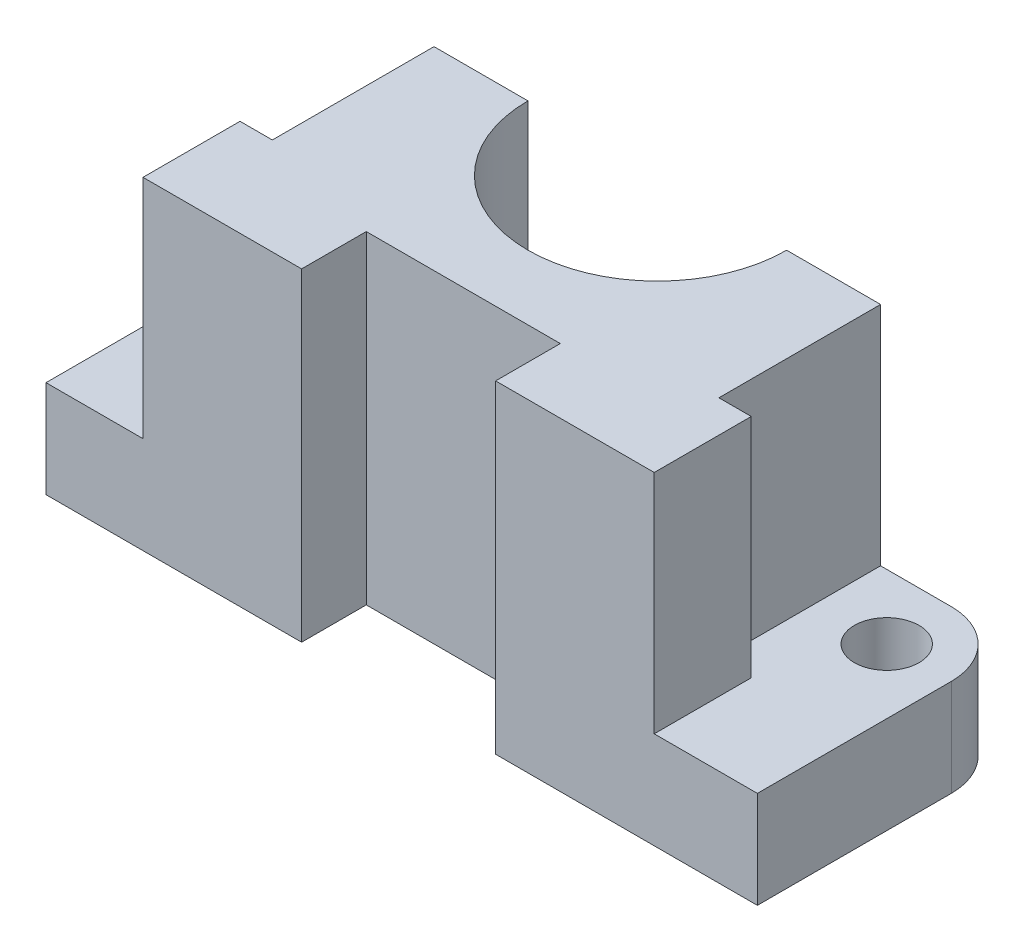
SolidWorks part; units mm, degrees
ref_plane "前视基准面" through (0, 0, 0) normal (0, 0, 1) x (1, 0, 0)
ref_plane "上视基准面" through (0, 0, 0) normal (0, 1, 0) x (1, 0, 0)
ref_plane "右视基准面" through (0, 0, 0) normal (1, 0, 0) x (0, 0, -1)
other "Configuration Table"
sketch "草图1" plane through (0, 0, 0) normal (0, 1, 0) x (1, 0, 0)
  line L0 (0, 0) -> (110, 0)
  line L1 (110, 0) -> (110, 30)
  line L2 (100, 40) -> (10, 40)
  line L3 (0, 30) -> (0, 0)
  arc A0 (110, 30) -> (100, 40) centre (100, 30) ccw
  arc A1 (10, 40) -> (0, 30) centre (10, 30) ccw
  circle A2 centre (10, 30) radius 5
  circle A3 centre (100, 30) radius 5
  point P9 (0, 40)
  dimension "D3" = 10
  dimension "D4" = 10
  dimension "D5" = 10
  dimension "D1" = 110
  dimension "D2" = 40
extrude "凸台-拉伸1" add sketch "草图1" along normal blind 50
sketch "草图2" plane through (0, 50, 0) normal (0, 1, 0) x (1, 0, 0)
  line L1 (54.5262, 40) -> (54.5262, 0)
  line L2 (39.5262, 0) -> (69.5262, 0)
  line L3 (69.5262, 0) -> (69.5262, 10)
  line L4 (69.5262, 10) -> (39.5262, 10)
  line L5 (0, 30) -> (0, 0)
  line L6 (0, 0) -> (110, 0)
  line L7 (110, 0) -> (110, 30)
  line L8 (100, 40) -> (10, 40)
  line L9 (0, 30) -> (0, 0)
  line L10 (0, 0) -> (110, 0)
  line L11 (110, 0) -> (110, 30)
  line L12 (100, 40) -> (10, 40)
  line L13 (39.5262, 0) -> (39.5262, 10)
  arc A2 (110, 30) -> (100, 40) centre (100, 30) ccw
  arc A3 (10, 40) -> (0, 30) centre (10, 30) ccw
  arc A4 (110, 30) -> (100, 40) centre (100, 30) ccw
  arc A5 (10, 40) -> (0, 30) centre (10, 30) ccw
  point P15 (54.5262, 10)
  line M3 (0, 0) -> (110, 0)
  dimension "D2" = 15
  dimension "D3" = 10
  dimension "D1" = 0
extrude "切除-拉伸1" cut sketch "草图2" against normal through all both and the other way through all contours L13 L1 L4 M3 | L3 L4 L1 M3
sketch "草图4" plane through (0, 50, 0) normal (0, 1, 0) x (1, 0, 0)
  line L0 (0, 0) -> (15, 0)
  line L1 (15, 0) -> (15, 15)
  line L2 (15, 15) -> (20, 15)
  line L3 (20, 15) -> (20, 40)
  line L4 (54.5262, 10) -> (54.5262, -2.2309) construction
  line L5 (89.0523, 15) -> (89.0523, 40)
  line L6 (94.0523, 15) -> (89.0523, 15)
  line L7 (94.0523, 0) -> (94.0523, 15)
  line L8 (0, 0) -> (39.5262, 0)
  line L9 (39.5262, 0) -> (39.5262, 10)
  line L10 (39.5262, 10) -> (69.5262, 10)
  line L11 (69.5262, 10) -> (69.5262, 0)
  line L12 (69.5262, 0) -> (110, 0)
  line L13 (110, 0) -> (110, 30)
  line L14 (100, 40) -> (10, 40)
  line L15 (0, 30) -> (0, 0)
  line L16 (0, 0) -> (39.5262, 0)
  line L17 (39.5262, 0) -> (39.5262, 10)
  line L18 (39.5262, 10) -> (69.5262, 10)
  line L19 (69.5262, 10) -> (69.5262, 0)
  line L20 (69.5262, 0) -> (110, 0)
  line L21 (110, 0) -> (110, 30)
  line L22 (100, 40) -> (10, 40)
  line L23 (0, 30) -> (0, 0)
  line L24 (109.0523, 0) -> (94.0523, 0)
  arc A2 (110, 30) -> (100, 40) centre (100, 30) ccw
  arc A3 (10, 40) -> (0, 30) centre (10, 30) ccw
  arc A4 (110, 30) -> (100, 40) centre (100, 30) ccw
  arc A5 (10, 40) -> (0, 30) centre (10, 30) ccw
  circle M16 centre (10, 30) radius 5
  circle M17 centre (100, 30) radius 5
  line M18 (0, 0) -> (39.5262, 0)
  line M22 (69.5262, 0) -> (110, 0)
  line M23 (110, 0) -> (110, 30)
  arc M24 (110, 30) -> (100, 40) centre (100, 30) ccw
  line M25 (100, 40) -> (10, 40)
  arc M26 (10, 40) -> (0, 30) centre (10, 30) ccw
  line M27 (0, 30) -> (0, 0)
  dimension "D2" = 15
  dimension "D3" = 15
  dimension "D4" = 5
  dimension "D1" = 0
extrude "切除-拉伸2" cut sketch "草图4" against normal blind 35 and the other way through all contours L2 L3 L1 M25 M26 M27 M18 M16 | L7 L20 L5 L6 M22 M23 M24 M25 M17
sketch "草图5" plane through (0, 50, 0) normal (0, 1, 0) x (1, 0, 0)
  line L0 (54.5262, 40) -> (54.5262, -5.9426)
  line L12 (69.5262, 0) -> (94.0523, 0)
  line L13 (94.0523, 0) -> (94.0523, 15)
  line L14 (94.0523, 15) -> (89.0523, 15)
  line L15 (89.0523, 15) -> (89.0523, 40)
  line L16 (89.0523, 40) -> (20, 40)
  line L17 (20, 40) -> (20, 15)
  line L18 (20, 15) -> (15, 15)
  line L19 (15, 15) -> (15, 0)
  line L20 (15, 0) -> (39.5262, 0)
  line L21 (39.5262, 0) -> (39.5262, 10)
  line L22 (39.5262, 10) -> (69.5262, 10)
  line L23 (69.5262, 10) -> (69.5262, 0)
  line L24 (69.5262, 0) -> (94.0523, 0)
  line L25 (94.0523, 0) -> (94.0523, 15)
  line L26 (94.0523, 15) -> (89.0523, 15)
  line L27 (89.0523, 15) -> (89.0523, 40)
  line L28 (89.0523, 40) -> (20, 40)
  line L29 (20, 40) -> (20, 15)
  line L30 (20, 15) -> (15, 15)
  line L31 (15, 15) -> (15, 0)
  line L32 (15, 0) -> (39.5262, 0)
  line L33 (39.5262, 0) -> (39.5262, 10)
  line L34 (39.5262, 10) -> (69.5262, 10)
  line L35 (69.5262, 10) -> (69.5262, 0)
  arc A0 (34.5262, 40) -> (74.5262, 40) centre (54.5262, 40) ccw
  arc A1 (44.5262, 40) -> (64.5262, 40) centre (54.5262, 40) ccw
  line M17 (89.0523, 40) -> (20, 40)
  dimension "D2" = 20
  dimension "D3" = 10
  dimension "D1" = 0
extrude "切除-拉伸3" cut sketch "草图5" against normal blind 20 contours A1 L0 A0 L28 | A1 L28 A0 L0 | A1 L0 M17 | L0 A1 M17
sketch "草图6" plane through (0, 30, 0) normal (0, 1, 0) x (1, 0, 0)
  line L1 (74.5262, 40) -> (34.5262, 40)
  line L2 (74.5262, 40) -> (34.5262, 40)
  arc A0 (44.5262, 40) -> (64.5262, 40) centre (54.5262, 40) ccw
  arc A1 (34.5262, 40) -> (74.5262, 40) centre (54.5262, 40) ccw
  arc A2 (34.5262, 40) -> (74.5262, 40) centre (54.5262, 40) ccw
  dimension "D2" = 20
  dimension "D1" = 0
extrude "切除-拉伸4" cut sketch "草图6" against normal through all contours L2 A0
